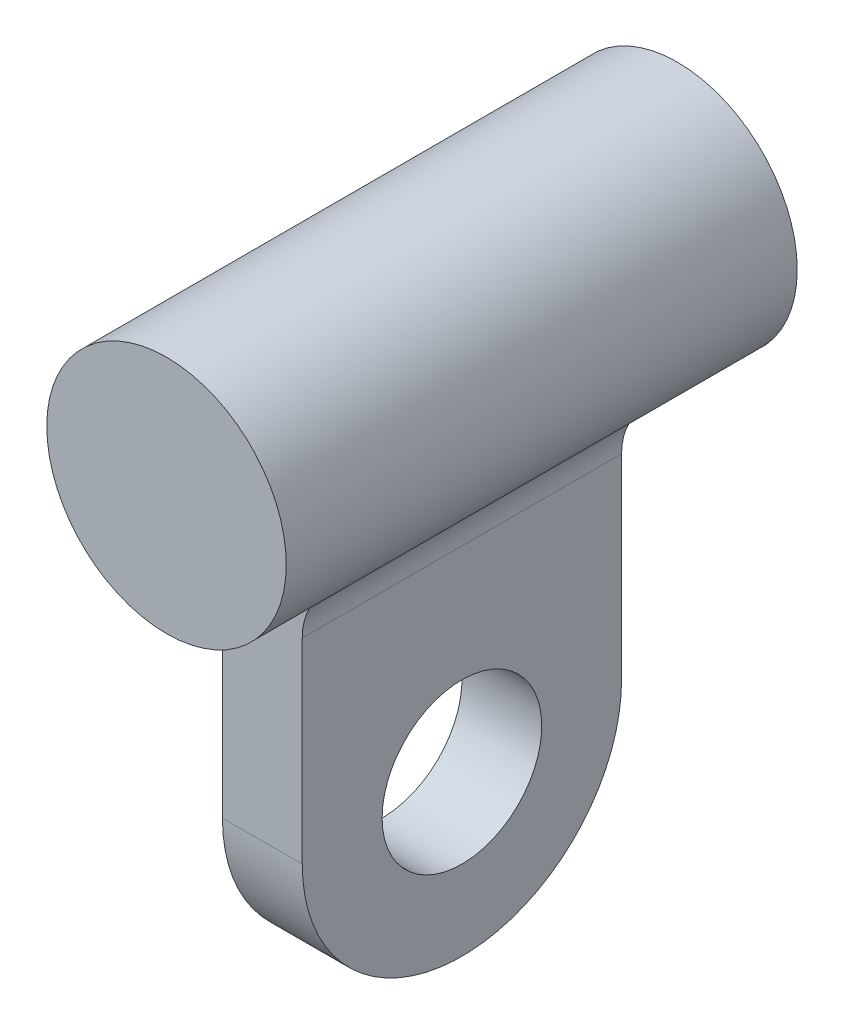
SolidWorks part; units mm, degrees
ref_plane "Front Plane" through (0, 0, 0) normal (0, 0, 1) x (1, 0, 0)
ref_plane "Top Plane" through (0, 0, 0) normal (0, 1, 0) x (1, 0, 0)
ref_plane "Right Plane" through (0, 0, 0) normal (1, 0, 0) x (0, 0, -1)
sketch "Sketch1" plane through (0, 0, 0) normal (0, 0, 1) x (1, 0, 0)
  circle A0 centre (-80.7816, -8.89) radius 4.7625
  dimension "D1" = 9.525
extrude "Boss-Extrude1" add sketch "Sketch1" along normal blind 20.32
ref_plane "Plane1" through (0, -10, 0) normal (0, 1, 0) x (1, 0, 0)
sketch "Sketch2" plane through (0, -10, 0) normal (0, 1, 0) x (1, 0, 0)
  line L0 (-74.4324, -20.32) -> (-87.1316, -20.32) construction
  line L1 (-79.1941, -3.81) -> (-82.3691, -3.81)
  line L2 (-79.1941, -3.81) -> (-79.1941, -16.51)
  line L3 (-79.1941, -16.51) -> (-82.3691, -16.51)
  line L4 (-82.3691, -3.81) -> (-82.3691, -16.51)
  line L8 (-76.0191, 0) -> (-76.0191, -20.32) construction
  dimension "D1" = 3.175
  dimension "D2" = 12.7
  dimension "D3" = 3.81
  dimension "D4" = 3.175
extrude "Boss-Extrude2" add sketch "Sketch2" against normal blind 19.05
sketch "Sketch3" plane through (-82.3691, 0, 0) normal (-1, 0, 0) x (0, 0, 1)
  line L0 (3.81, -29.05) -> (3.81, -13.3801) construction
  line L1 (3.81, -29.05) -> (16.51, -29.05) construction
  line L2 (16.51, -29.05) -> (16.51, -13.3801) construction
  line L3 (3.81, -22.7) -> (3.81, -29.05)
  line L4 (3.81, -29.05) -> (10.16, -29.05)
  line L5 (10.16, -29.05) -> (16.51, -29.05)
  line L6 (16.51, -29.05) -> (16.51, -22.7)
  arc A0 (3.81, -22.7) -> (16.51, -22.7) centre (10.16, -22.7) ccw
  line M2 (3.81, -13.3801) -> (3.81, -29.05)
  line M3 (3.81, -29.05) -> (16.51, -29.05)
  line M4 (16.51, -29.05) -> (16.51, -13.3801)
extrude "Cut-Extrude1" cut sketch "Sketch3" against normal through all contours A0 M3 M4 | A0 M2 M3
sketch "Sketch4" plane through (-82.3691, 0, 0) normal (-1, 0, 0) x (0, 0, 1)
  circle A0 centre (10.16, -22.7) radius 3.175
  dimension "D1" = 6.35
extrude "Cut-Extrude2" cut sketch "Sketch4" against normal through all
fillet "Fillet1" radius 2.54 2 edges at (-79.1941, -13.3801, 10.16) (-82.3691, -13.3801, 10.16)
